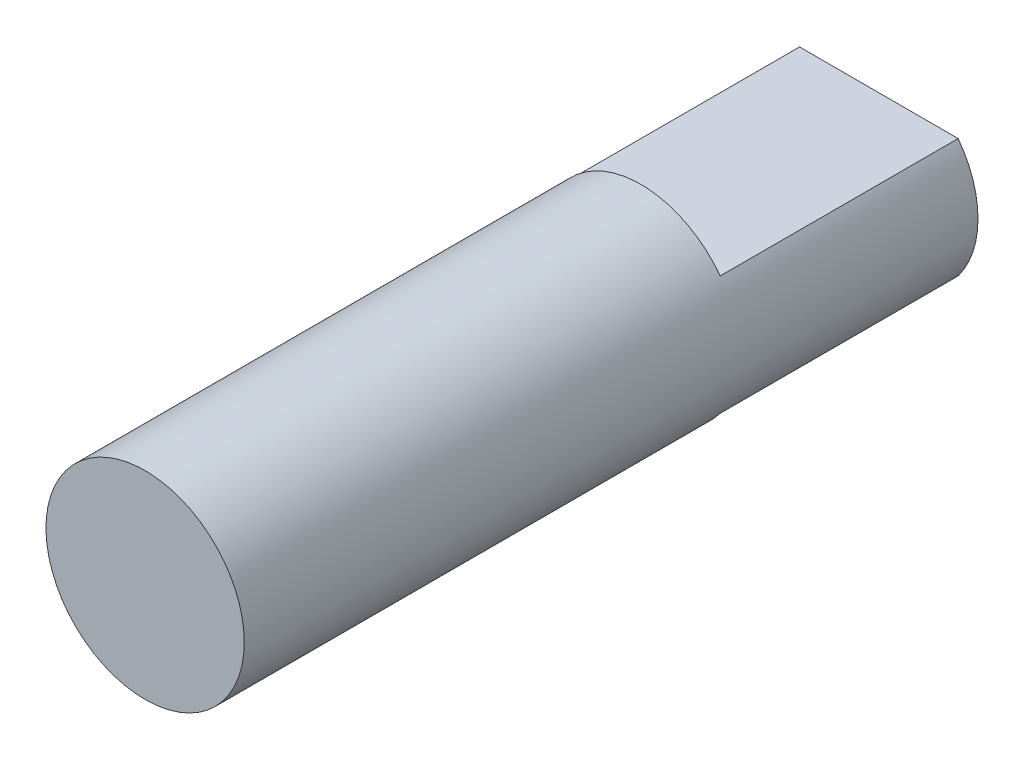
SolidWorks part; units mm, degrees
ref_plane "Plan de face" through (0, 0, 0) normal (0, 0, 1) x (1, 0, 0)
ref_plane "Plan de dessus" through (0, 0, 0) normal (0, 1, 0) x (1, 0, 0)
ref_plane "Plan de droite" through (0, 0, 0) normal (1, 0, 0) x (0, 0, -1)
sketch "Esquisse1" plane through (0, 0, 0) normal (0, 0, 1) x (1, 0, 0)
  circle A0 centre (0, 0) radius 2.5
  dimension "D1" = 5
extrude "Boss.-Extru.1" add sketch "Esquisse1" along normal blind 18.5
sketch "Esquisse2" plane through (0, 0, 0) normal (0, 0, 1) x (1, 0, 0)
  line L0 (-2, 1.5) -> (2, 1.5)
  line L1 (-2, -1.5) -> (2, -1.5)
  circle A0 centre (0, 0) radius 2.5 construction
  arc A1 (-2, -1.5) -> (2, -1.5) centre (0, 0) ccw
  arc A2 (2, 1.5) -> (-2, 1.5) centre (0, 0) ccw
  dimension "D1" = 1.5
  dimension "D2" = 1.5
extrude "Enlèv. mat.-Extru.1" cut sketch "Esquisse2" along normal blind 6 contours L0 A2 | L1 A1
